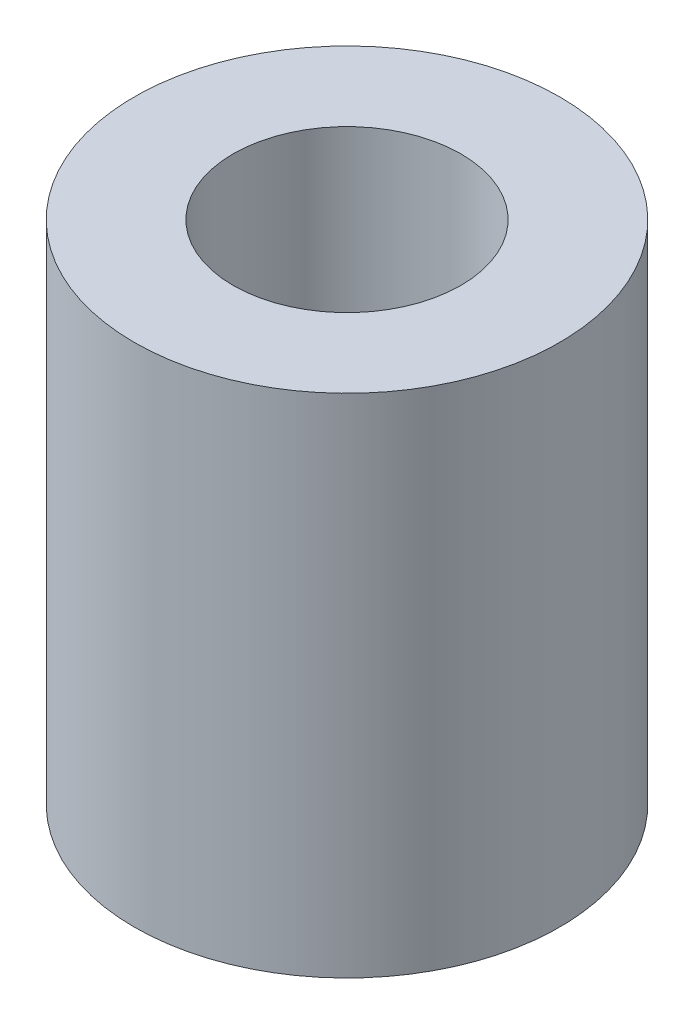
SolidWorks part; units mm, degrees
ref_plane "Front Plane" through (0, 0, 0) normal (0, 0, 1) x (1, 0, 0)
ref_plane "Top Plane" through (0, 0, 0) normal (0, 1, 0) x (1, 0, 0)
ref_plane "Right Plane" through (0, 0, 0) normal (1, 0, 0) x (0, 0, -1)
sketch "Sketch1" plane through (0, 0, 0) normal (0, 1, 0) x (1, 0, 0)
  circle A0 centre (0, 0) radius 2.25
  circle A1 centre (0, 0) radius 4.2
  dimension "D1" = 4.5
  dimension "D2" = 8.4
extrude "Boss-Extrude1" add sketch "Sketch1" along normal blind 10
